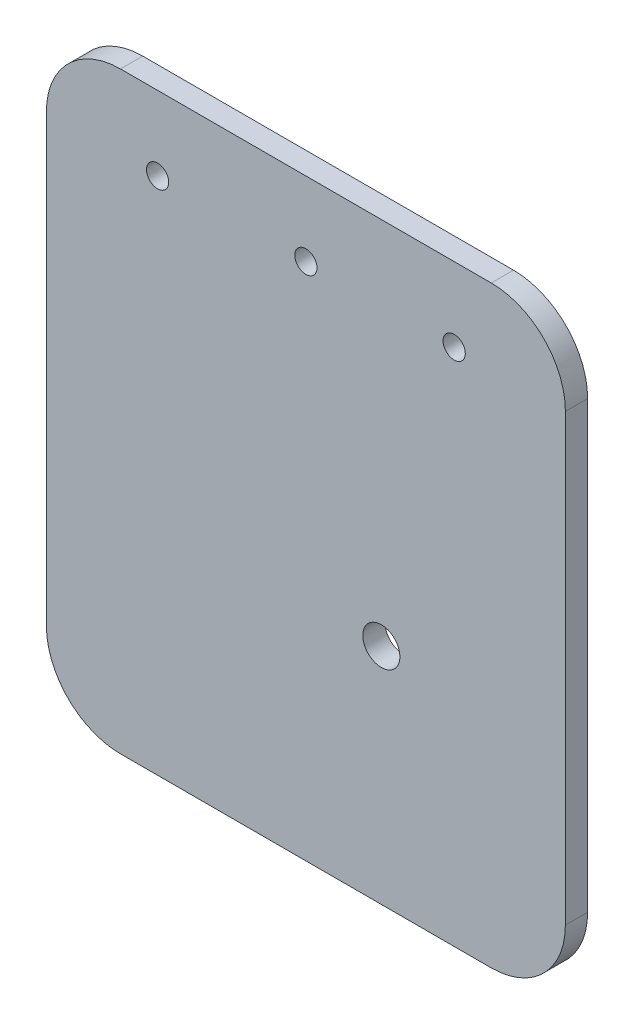
SolidWorks part; units mm, degrees
ref_plane "前视基准面" through (0, 0, 0) normal (0, 0, 1) x (1, 0, 0)
ref_plane "上视基准面" through (0, 0, 0) normal (0, 1, 0) x (1, 0, 0)
ref_plane "右视基准面" through (0, 0, 0) normal (1, 0, 0) x (0, 0, -1)
sketch "草图1" plane through (0, 0, 0) normal (0, 0, 1) x (1, 0, 0)
  line L1 (-35, 40) -> (35, 40)
  line L2 (-35, 40) -> (-35, -40)
  line L3 (-35, -40) -> (35, -40)
  line L4 (35, 40) -> (35, -40)
  line L5 (-35, 40) -> (35, -40) construction
  line L6 (-35, -40) -> (35, 40) construction
  point P0 (0, 0)
  dimension "D1" = 70
  dimension "D2" = 80
extrude "凸台-拉伸1" add sketch "草图1" along normal blind 3
sketch "草图2" plane through (0, 0, 0) normal (0, 0, -1) x (-1, 0, 0)
  circle A0 centre (-10.175, -9.825) radius 2.5
  dimension "D1" = 5
extrude "切除-拉伸1" cut sketch "草图2" against normal blind 10
sketch "草图3" plane through (0, 0, 3) normal (0, 0, 1) x (1, 0, 0)
  line L0 (35, 40) -> (-35, 40) construction
  line L1 (35, -40) -> (35, 40) construction
  line L2 (-35, 40) -> (-35, -40) construction
  circle A0 centre (0, 30) radius 1.5
  circle A1 centre (20, 30) radius 1.5
  circle A2 centre (-20, 30) radius 1.5
  dimension "D1" = 3
  dimension "D2" = 3
  dimension "D3" = 3
  dimension "D4" = 10
  dimension "D5" = 15
  dimension "D6" = 15
extrude "切除-拉伸2" cut sketch "草图3" against normal blind 10
fillet "圆角1" radius 10 4 edges at (35, -40, 1.5) (-35, -40, 1.5) (-35, 40, 1.5) (35, 40, 1.5)
